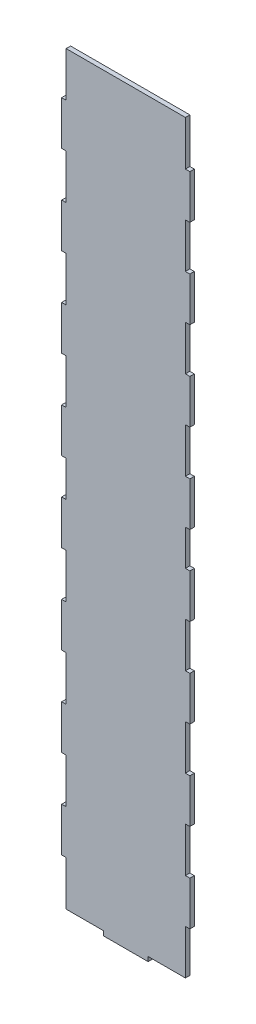
SolidWorks part; units mm, degrees
ref_plane "Plano frontal" through (0, 0, 0) normal (0, 0, 1) x (1, 0, 0)
ref_plane "Plano superior" through (0, 0, 0) normal (0, 1, 0) x (1, 0, 0)
ref_plane "Plano direito" through (0, 0, 0) normal (1, 0, 0) x (0, 0, -1)
sketch "Esboço1" plane through (0, 0, 0) normal (0, 0, 1) x (1, 0, 0)
  line L0 (40, 0) -> (-40, 0) construction
  line L1 (-40, -250) -> (-15, -250)
  line L2 (-40, -250) -> (-40, -220)
  line L3 (-40, 250) -> (40, 250)
  line L4 (40, -250) -> (40, -220)
  line L5 (-40, -250) -> (40, 250) construction
  line L6 (-40, 250) -> (40, -250) construction
  line L7 (-40, 220) -> (-43, 220)
  line L9 (-40, 190.5) -> (-43, 190.5)
  line L10 (-43, 220) -> (-43, 190.5)
  line L11 (-43, 160.5) -> (-40, 160.5)
  line L12 (-43, 160.5) -> (-43, 131)
  line L13 (-43, 131) -> (-40, 131)
  line L15 (-40, 101) -> (-43, 101)
  line L17 (-40, 71.5) -> (-43, 71.5)
  line L18 (-43, 101) -> (-43, 71.5)
  line L19 (-40, 41.5) -> (-43, 41.5)
  line L21 (-40, 12) -> (-43, 12)
  line L22 (-43, 41.5) -> (-43, 12)
  line L23 (-40, -190.5) -> (-43, -190.5)
  line L24 (-43, -220) -> (-43, -190.5)
  line L25 (-40, -220) -> (-43, -220)
  line L27 (-43, -131) -> (-40, -131)
  line L29 (-43, -160.5) -> (-40, -160.5)
  line L30 (-43, -160.5) -> (-43, -131)
  line L31 (-40, -71.5) -> (-43, -71.5)
  line L32 (-43, -101) -> (-43, -71.5)
  line L33 (-40, -101) -> (-43, -101)
  line L35 (-40, -12) -> (-43, -12)
  line L36 (-43, -41.5) -> (-43, -12)
  line L37 (-40, -41.5) -> (-43, -41.5)
  line L39 (0, -250) -> (0, 250) construction
  line L41 (-15, -250) -> (-15, -253)
  line L42 (-15, -253) -> (15, -253)
  line L43 (15, -250) -> (15, -253)
  line L45 (40, -220) -> (43, -220)
  line L46 (43, -220) -> (43, -190.5)
  line L47 (40, -190.5) -> (43, -190.5)
  line L48 (43, -160.5) -> (43, -131)
  line L49 (43, -160.5) -> (40, -160.5)
  line L51 (43, -131) -> (40, -131)
  line L53 (40, -101) -> (43, -101)
  line L54 (43, -101) -> (43, -71.5)
  line L55 (40, -71.5) -> (43, -71.5)
  line L57 (40, -41.5) -> (43, -41.5)
  line L58 (43, -41.5) -> (43, -12)
  line L59 (40, -12) -> (43, -12)
  line L60 (40, 12) -> (43, 12)
  line L61 (43, 41.5) -> (43, 12)
  line L62 (40, 41.5) -> (43, 41.5)
  line L64 (40, 71.5) -> (43, 71.5)
  line L65 (43, 101) -> (43, 71.5)
  line L66 (40, 101) -> (43, 101)
  line L68 (43, 131) -> (40, 131)
  line L70 (43, 160.5) -> (40, 160.5)
  line L71 (43, 160.5) -> (43, 131)
  line L72 (40, 190.5) -> (43, 190.5)
  line L73 (43, 220) -> (43, 190.5)
  line L74 (40, 220) -> (43, 220)
  line L76 (15, -250) -> (40, -250)
  line L77 (-40, -190.5) -> (-40, -160.5)
  line L78 (40, -190.5) -> (40, -160.5)
  line L79 (-40, -131) -> (-40, -101)
  line L80 (-40, -71.5) -> (-40, -41.5)
  line L81 (-40, -12) -> (-40, 12)
  line L82 (-40, 41.5) -> (-40, 71.5)
  line L83 (-40, 101) -> (-40, 131)
  line L84 (-40, 160.5) -> (-40, 190.5)
  line L85 (-40, 220) -> (-40, 250)
  line L86 (40, 220) -> (40, 250)
  line L87 (40, 160.5) -> (40, 190.5)
  line L88 (40, 101) -> (40, 131)
  line L89 (40, 41.5) -> (40, 71.5)
  line L90 (40, -12) -> (40, 12)
  line L91 (40, -71.5) -> (40, -41.5)
  line L92 (40, -131) -> (40, -101)
  line L93 (-15, -250) -> (15, -250) construction
  point P0 (0, 0)
  point P78 (0, -244.3139)
  point P79 (0, -250)
  dimension "D1" = 80
  dimension "D2" = 500
  dimension "D3" = 3
  dimension "D4" = 29.5
  dimension "D5" = 30
  dimension "D6" = 3
  dimension "D7" = 29.5
  dimension "D8" = 30
  dimension "D9" = 30
  dimension "D10" = 29.5
  dimension "D11" = 3
  dimension "D12" = 3
  dimension "D13" = 29.5
  dimension "D14" = 30
  dimension "D15" = 3
  dimension "D16" = 30
  dimension "D17" = 25
  dimension "D18" = 24
extrude "Ressalto-extrusão1" add sketch "Esboço1" along normal blind 3
